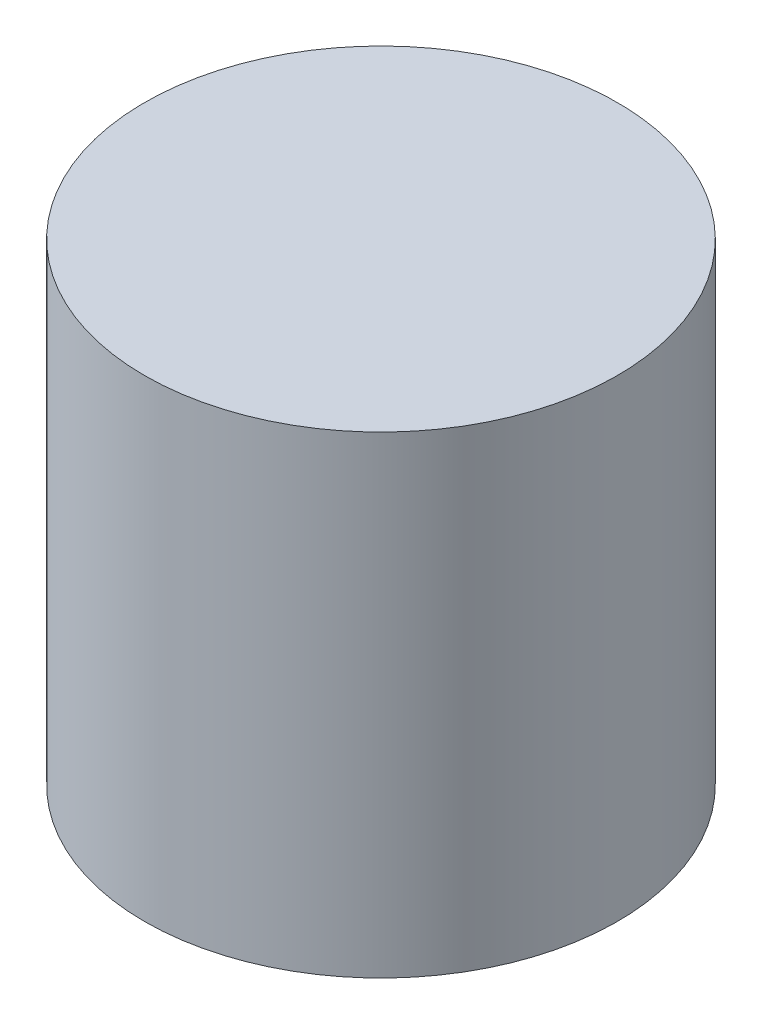
SolidWorks part; units mm, degrees
ref_plane "前基準面" through (0, 0, 0) normal (0, 0, 1) x (1, 0, 0)
ref_plane "上基準面" through (0, 0, 0) normal (0, 1, 0) x (1, 0, 0)
ref_plane "右基準面" through (0, 0, 0) normal (1, 0, 0) x (0, 0, -1)
sketch "草圖1" plane through (0, 0, 0) normal (0, 1, 0) x (1, 0, 0)
  circle A0 centre (0, 0) radius 7.5
  dimension "D1" = 15
extrude "填料-伸長1" add sketch "草圖1" along normal blind 15
